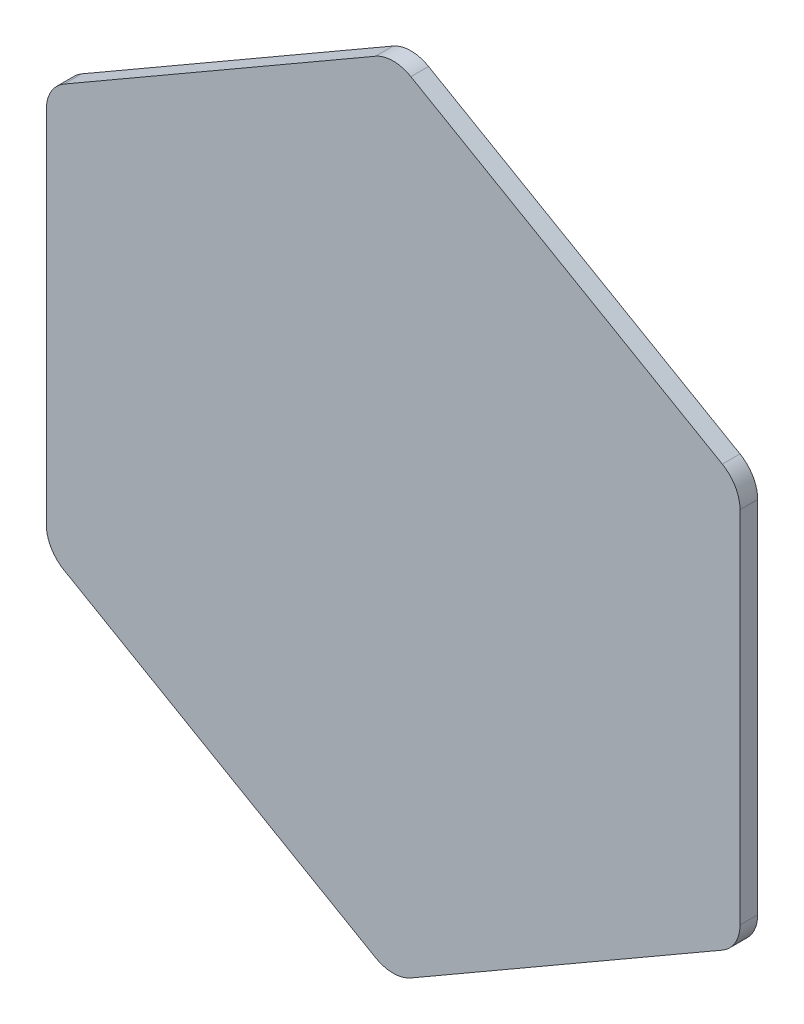
SolidWorks part; units mm, degrees
ref_plane "前视基准面" through (0, 0, 0) normal (0, 0, 1) x (1, 0, 0)
ref_plane "上视基准面" through (0, 0, 0) normal (0, 1, 0) x (1, 0, 0)
ref_plane "右视基准面" through (0, 0, 0) normal (1, 0, 0) x (0, 0, -1)
sketch "草图1" plane through (0, 0, 0) normal (0, 0, 1) x (1, 0, 0)
  line L1 (0, 11.32) -> (-9.8034, 5.66)
  line L2 (-9.8034, 5.66) -> (-9.8034, -5.66)
  line L3 (-9.8034, -5.66) -> (0, -11.32)
  line L4 (0, -11.32) -> (9.8034, -5.66)
  line L5 (9.8034, -5.66) -> (9.8034, 5.66)
  line L6 (9.8034, 5.66) -> (0, 11.32)
  circle A0 centre (0, 0) radius 11.32 construction
extrude "凸台-拉伸1" add sketch "草图1" along normal blind 0.5
fillet "圆角1" radius 1 6 edges at (9.8034, 5.66, 0.25) (9.8034, -5.66, 0.25) (0, -11.32, 0.25) (-9.8034, -5.66, 0.25) (-9.8034, 5.66, 0.25) (0, 11.32, 0.25)
sketch "草图3" plane through (0, 0, 0) normal (0, 0, 1) x (1, 0, 0)
  line L49 (-6.6616, 4.0263) -> (-3.7118, 2.8674)
  line L50 (-6.6616, 4.0263) -> (-6.6616, 6.9354)
  line L51 (-6.6616, 6.9354) -> (-0.7055, 4.5956)
  line L52 (4.9345, 6.0297) -> (2.0596, 4.9008)
  line L53 (4.9345, 6.0297) -> (4.9345, 3.1385)
  line L54 (3.5274, 2.5778) -> (-0.8358, 0.8389)
  line L55 (4.0371, 2.0515) -> (1.1463, 0.9453)
  line L56 (-1.5508, 3.483) -> (-1.9038, 3.3444)
  line L57 (2.0596, 4.9008) -> (-1.5508, 3.483)
  line L58 (4.9345, 3.1385) -> (3.5274, 2.5778)
  arc A6 (-0.2778, 1.0613) -> (1.1463, 0.9453) centre (0.2625, -1.1056) ccw
  arc A7 (-1.5508, 3.483) -> (4.0371, 2.0515) centre (0.2511, -1.1055) ccw
  arc A8 (-0.7055, 4.5956) -> (-3.7118, 2.8674) centre (1.5016, -2.7228) ccw
  point P0 (0, 0)
sketch "草图4" plane through (0, 0, 0) normal (0, 0, 1) x (1, 0, 0)
  line L49 (-9.2674, 131.6793) -> (-4.6222, 129.8544)
  line L50 (-9.2674, 131.6793) -> (-9.2674, 136.2605)
  line L51 (-9.2674, 136.2605) -> (0.1119, 132.5758)
  line L52 (8.9936, 134.8343) -> (4.4663, 133.0564)
  line L53 (8.9936, 134.8343) -> (8.9936, 130.2813)
  line L54 (6.7778, 129.3983) -> (-0.0932, 126.6599)
  line L55 (7.5805, 128.5696) -> (3.0281, 126.8274)
  line L56 (-1.2192, 130.8238) -> (-1.7751, 130.6055)
  line L57 (4.4663, 133.0564) -> (-1.2192, 130.8238)
  line L58 (8.9936, 130.2813) -> (6.7778, 129.3983)
  arc A6 (0.7856, 127.0101) -> (3.0281, 126.8274) centre (1.6363, 123.5979) ccw
  arc A7 (-1.2192, 130.8238) -> (7.5805, 128.5696) centre (1.6184, 123.598) ccw
  arc A8 (0.1119, 132.5758) -> (-4.6222, 129.8544) centre (3.5877, 121.0511) ccw
extrude "凸台-拉伸3" add sketch "草图3" against normal blind 0.5 contours A8 L51 L50 L49 | L57 A7 L55 A6 L54 L58 L53 L52
